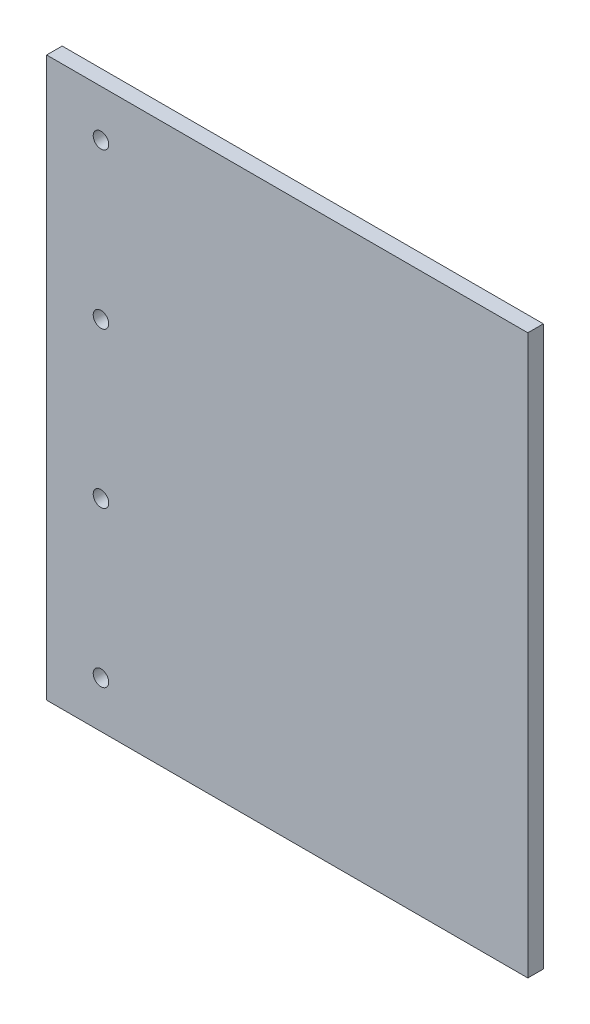
SolidWorks part; units mm, degrees
ref_plane "Front Plane" through (0, 0, 0) normal (0, 0, 1) x (1, 0, 0)
ref_plane "Top Plane" through (0, 0, 0) normal (0, 1, 0) x (1, 0, 0)
ref_plane "Right Plane" through (0, 0, 0) normal (1, 0, 0) x (0, 0, -1)
sketch "Sketch1" plane through (0, 0, 0) normal (0, 0, 1) x (1, 0, 0)
  line L1 (0, 0) -> (393.7, 0)
  line L2 (0, 0) -> (0, 457.2)
  line L3 (0, 457.2) -> (393.7, 457.2)
  line L4 (393.7, 0) -> (393.7, 457.2)
  dimension "D1" = 393.7
  dimension "D2" = 457.2
extrude "Plate" add sketch "Sketch1" along normal blind 12.7
hole_wizard "Hole" positions "Sketch4" profile "Sketch3" hole size "1/2" standard "Ansi Inch"
sketch "Sketch4" plane through (0, 0, 12.7) normal (0, 0, 1) x (1, 0, 0)
  line L0 (0, 457.2) -> (0, 0) construction
  line L1 (0, 0) -> (393.7, 0) construction
  point P0 (44.45, 38.1)
  dimension "D1" = 44.45
  dimension "D2" = 38.1
sketch "Sketch3" plane through (44.45, 38.1, 12.7) normal (1, 0, 0) x (0, -1, 0)
  line L0 (0, 0) -> (0, 29.2155)
  line L1 (0, 29.2155) -> (6.35, 25.4)
  line L2 (6.35, 25.4) -> (6.35, 0)
  line L5 (6.35, 0) -> (0, 0)
  line L10 (0, 29.2155) -> (-6.35, 25.4) construction
  line L11 (0, -6.35) -> (0, 107.95) construction
  dimension "Hole Dia." = 12.7
  dimension "Hole Depth" = 25.4
  dimension "Drill Angle" = 118
pattern_linear "標準複製排列" count 4 spacing 127 along (0, 1, 0) of "Hole"
